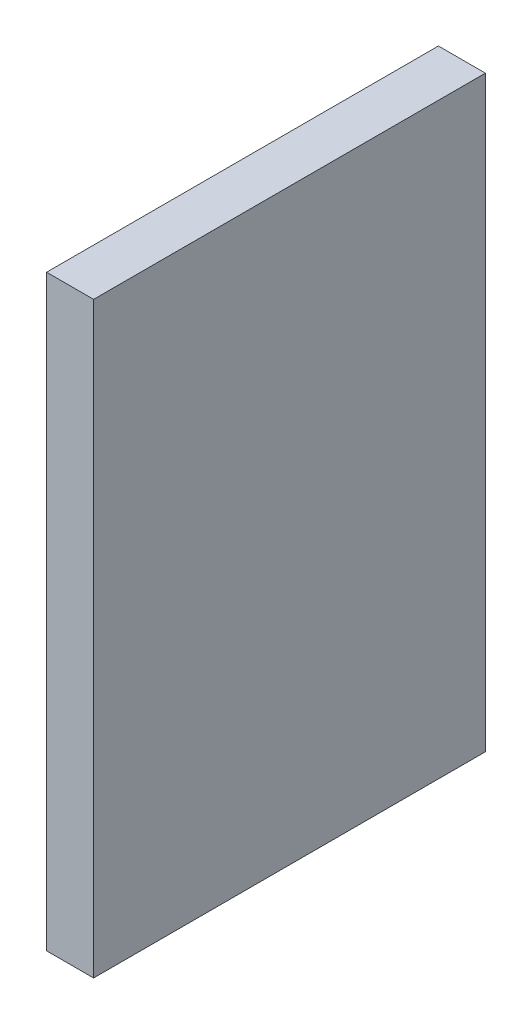
SolidWorks part; units mm, degrees
ref_plane "Front Plane" through (0, 0, 0) normal (1, 0, 0) x (0, 1, 0)
ref_plane "Top Plane" through (0, 0, 0) normal (0, 0, 1) x (0, 1, 0)
ref_plane "Right Plane" through (0, 0, 0) normal (0, 1, 0) x (-1, 0, 0)
sketch "Sketch1" plane through (0, 0, 0) normal (1, 0, 0) x (0, 1, 0)
  line L1 (-75, -50) -> (75, -50)
  line L2 (-75, -50) -> (-75, 50)
  line L3 (-75, 50) -> (75, 50)
  line L4 (75, -50) -> (75, 50)
  line L5 (-75, -50) -> (75, 50) construction
  line L6 (-75, 50) -> (75, -50) construction
  point P0 (0, 0)
extrude "Boss-Extrude1" add sketch "Sketch1" along normal blind 12
